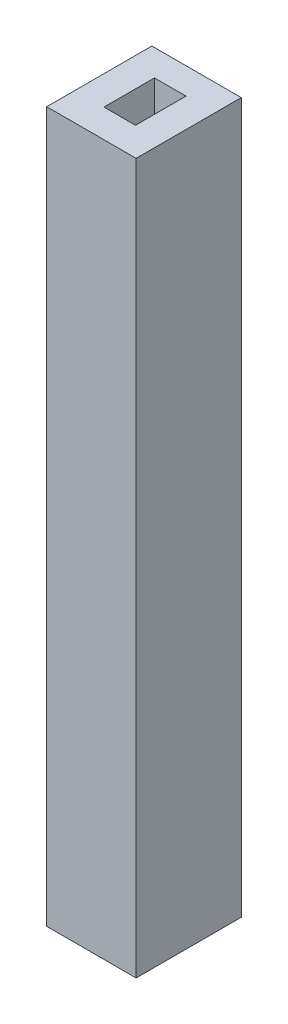
SolidWorks part; units mm, degrees
ref_plane "정면" through (0, 0, 0) normal (0, 0, 1) x (1, 0, 0)
ref_plane "윗면" through (0, 0, 0) normal (0, 1, 0) x (1, 0, 0)
ref_plane "우측면" through (0, 0, 0) normal (1, 0, 0) x (0, 0, -1)
sketch "스케치1" plane through (0, 0, 0) normal (1, 0, 0) x (0, 0, -1)
  line L0 (0, -135) -> (0, 0) construction
  line L1 (-20, -270) -> (20, -270)
  line L2 (-20, -270) -> (-20, 0)
  line L3 (-20, 0) -> (20, 0)
  line L4 (20, -270) -> (20, 0)
  line L5 (-20, -270) -> (20, 0) construction
  line L6 (-20, 0) -> (20, -270) construction
  point P0 (0, -135)
  dimension "D1" = 270
  dimension "D2" = 40
extrude "보스-돌출1" add sketch "스케치1" along normal mid plane 34
sketch "스케치2" plane through (0, 0, 0) normal (1, 0, 0) x (0, 0, -1)
  line L0 (-9.2313, 0) -> (-9.2313, -13.5184)
  line L1 (20, 0) -> (-20, 0) construction
  line L2 (-9.2313, -13.5184) -> (-5.0208, -120)
  line L3 (-5.0208, -120) -> (9.9792, -120)
  line L4 (9.9792, -120) -> (9.9792, 0)
  line L5 (9.9792, 0) -> (-9.2313, 0)
  dimension "D1" = 120
  dimension "D2" = 15
extrude "컷-돌출1" cut sketch "스케치2" against normal mid plane 12
sketch "스케치3" plane through (0, 0, 0) normal (1, 0, 0) x (0, 0, -1)
  line L1 (-66.334, 26.0969) -> (85.9402, 26.0969)
  line L2 (-66.334, 26.0969) -> (-66.334, -328.7738)
  line L3 (-66.334, -328.7738) -> (85.9402, -328.7738)
  line L4 (85.9402, 26.0969) -> (85.9402, -328.7738)
